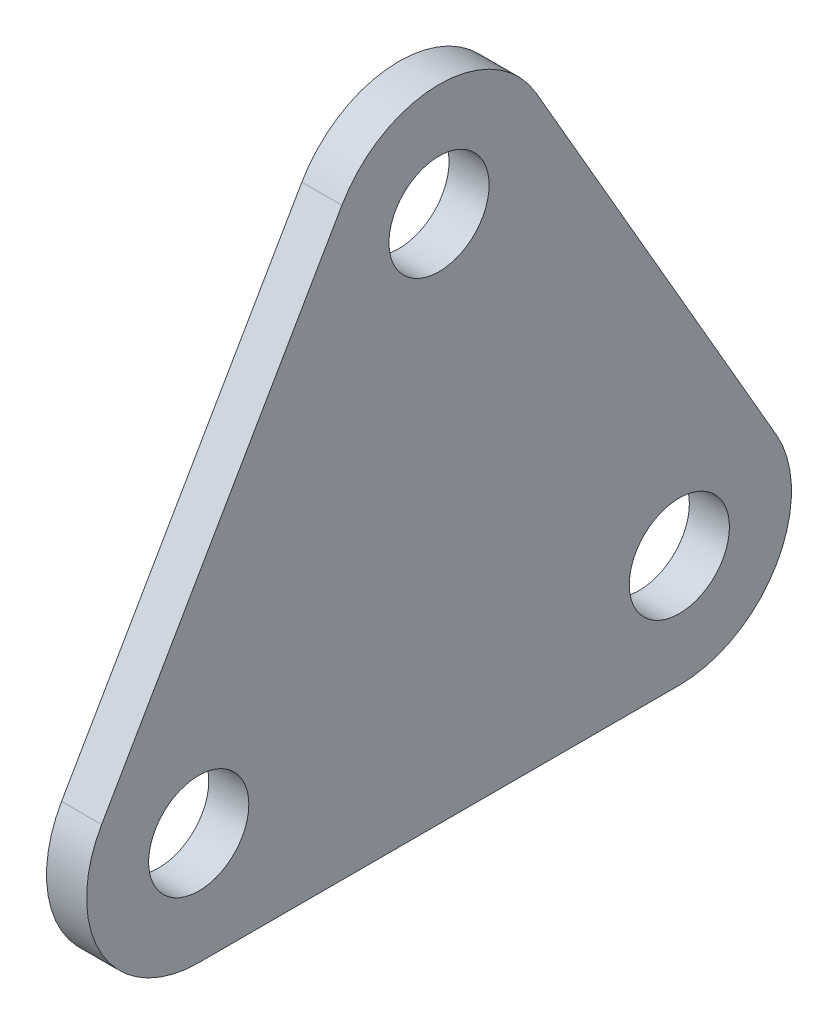
SolidWorks part; units mm, degrees
ref_plane "Front Plane" through (0, 0, 0) normal (0, 0, 1) x (1, 0, 0)
ref_plane "Top Plane" through (0, 0, 0) normal (0, 1, 0) x (1, 0, 0)
ref_plane "Right Plane" through (0, 0, 0) normal (1, 0, 0) x (0, 0, -1)
sketch "Sketch1" plane through (0, 0, 0) normal (1, 0, 0) x (0, 0, -1)
  line L0 (-65.5347, -10.7274) -> (-41.5453, 30.8237) construction
  line L1 (-31.8508, 36.4208) -> (-7.8613, -5.1302)
  line L2 (-17.5558, -21.9216) -> (-65.5347, -21.9216)
  line L3 (-75.2292, -5.1302) -> (-51.2398, 36.4208)
  line L4 (-41.5453, 30.8237) -> (-17.5558, -10.7274) construction
  line L5 (-17.5558, -10.7274) -> (-65.5347, -10.7274) construction
  arc A0 (-7.8613, -5.1302) -> (-17.5558, -21.9216) centre (-17.5558, -10.7274) cw
  arc A2 (-31.8508, 36.4208) -> (-51.2398, 36.4208) centre (-41.5453, 30.8237) ccw
  arc A3 (-75.2292, -5.1302) -> (-65.5347, -21.9216) centre (-65.5347, -10.7274) ccw
  circle A4 centre (-41.5453, 30.8237) radius 5
  circle A6 centre (-17.5558, -10.7274) radius 5
  circle A7 centre (-65.5347, -10.7274) radius 5
extrude "Boss-Extrude1" add sketch "Sketch1" along normal blind 4
